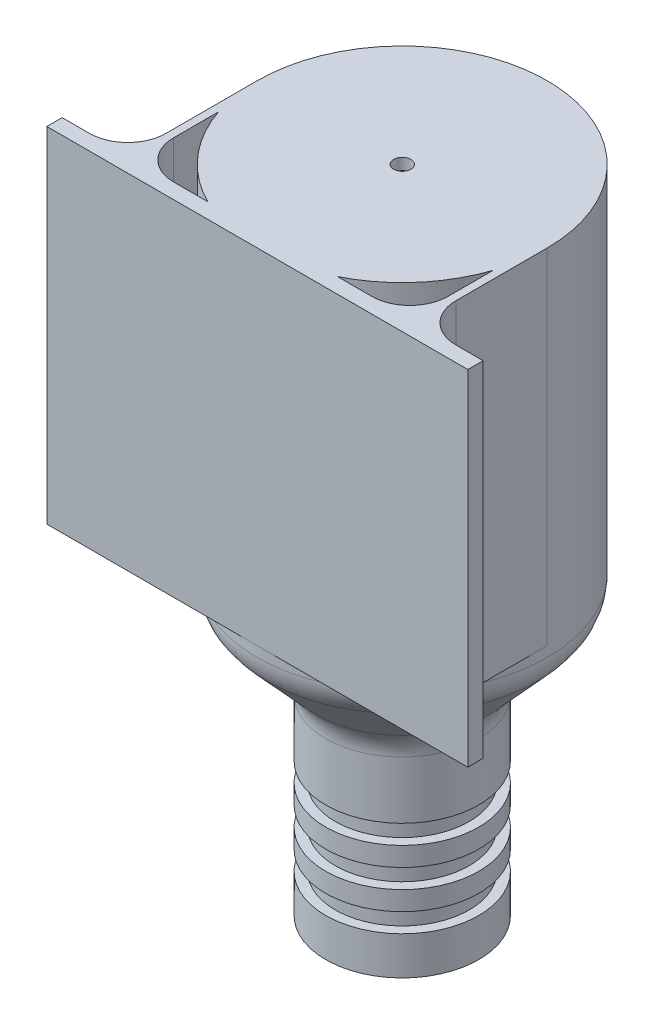
SolidWorks part; units mm, degrees
ref_plane "前视基准面" through (0, 0, 0) normal (0, 0, 1) x (1, 0, 0)
ref_plane "上视基准面" through (0, 0, 0) normal (0, 1, 0) x (1, 0, 0)
ref_plane "右视基准面" through (0, 0, 0) normal (1, 0, 0) x (0, 0, -1)
other "Configuration Table"
sketch "草图2" plane through (0, 0, 0) normal (0, 0, 1) x (1, 0, 0)
  line L0 (0, -59.8968) -> (0, -239.7168) construction
  line L1 (20, -224.4112) -> (20, -214.4112)
  line L2 (20, -214.4112) -> (17.5, -214.4112)
  line L3 (17.5, -214.4112) -> (17.5, -209.4112)
  line L4 (17.5, -209.4112) -> (20, -209.4112)
  line L5 (20, -209.4112) -> (20, -204.4112)
  line L6 (20, -204.4112) -> (17.5, -204.4112)
  line L7 (17.5, -204.4112) -> (17.5, -199.4112)
  line L8 (17.5, -199.4112) -> (20, -199.4112)
  line L9 (20, -199.4112) -> (20, -194.4112)
  line L10 (20, -194.4112) -> (17.5, -194.4112)
  line L11 (17.5, -194.4112) -> (17.5, -189.4112)
  line L12 (17.5, -189.4112) -> (20, -189.4112)
  line L13 (15.5, -224.4112) -> (15.5, -174.7923)
  line L16 (15.5, -224.4112) -> (20, -224.4112)
  line L17 (20, -189.4112) -> (20, -174.4112)
  line L18 (18.5713, -167.5817) -> (20.5164, -165.7126)
  line L19 (35.8731, -129.6594) -> (35.8731, -54.4112)
  line L20 (22.615, -167.6687) -> (35.2581, -153.8207)
  line L21 (37.8731, -147.0782) -> (37.8731, -54.4112)
  line L22 (37.8731, -54.4112) -> (35.8731, -54.4112)
  arc A0 (20.5164, -165.7126) -> (35.8731, -129.6594) centre (-14.1269, -129.6594) ccw
  arc A1 (35.2581, -153.8207) -> (37.8731, -147.0782) centre (27.8731, -147.0782) ccw
  arc A2 (15.5, -174.7923) -> (18.5713, -167.5817) centre (25.5, -174.7923) cw
  arc A3 (20, -174.4112) -> (22.615, -167.6687) centre (30, -174.4112) cw
  point P2 (0, 0)
  point P24 (0, 0)
  point P25 (0, 0)
  point P26 (15.8596, -172.1504)
  point P27 (18.2503, -189.4112)
  point P28 (35.8731, -152.574)
  point P31 (35.8731, -150.9565)
  point P34 (37.8731, -150.9565)
  point P37 (15.5, -170.5329)
  point P40 (20, -170.5329)
  point P41 (0, 0)
  point P42 (0, 0)
  point P43 (19.88, -226.0579)
  dimension "D13" = 50
  dimension "D14" = 10
  dimension "D15" = 10
  dimension "D2" = 2.5
  dimension "D3" = 5
  dimension "D4" = 2.5
  dimension "D5" = 5
  dimension "D6" = 2.5
  dimension "D7" = 5
  dimension "D8" = 5
  dimension "D9" = 10
  dimension "D10" = 5
  dimension "D11" = 2
  dimension "D12" = 2.5
  dimension "D16" = 120
  dimension "D17" = 50
  dimension "D18" = 40
  dimension "D19" = 2
revolve "旋转1" add sketch "草图2" angle 360 about L0
sketch "草图3" plane through (0, -54.4112, 0) normal (0, 1, 0) x (1, 0, 0)
  line L0 (0, 51.2049) -> (0, -52.2438) construction
  circle A1 centre (0, 0) radius 2.25
  circle A2 centre (0, 0) radius 37.8731 construction
  circle A4 centre (0, 0) radius 37.8731
  circle M1 centre (0, 0) radius 35.8731
  circle M2 centre (0, 0) radius 37.8731
  dimension "D1" = 4.5
sketch "草图4" plane through (0, -54.4112, 0) normal (0, 1, 0) x (1, 0, 0)
  line L0 (-37.8731, 0) -> (-37.8731, -23.8731)
  line L1 (-47.8731, -33.8731) -> (-55, -33.8731)
  line L2 (-55, -33.8731) -> (-55, -37.8731)
  line L3 (-55, -37.8731) -> (55, -37.8731)
  line L4 (0, 51.2049) -> (0, -52.2438) construction
  line L5 (0, -37.8731) -> (0, -33.8731) construction
  line L6 (25.8731, -33.8731) -> (-25.8731, -33.8731)
  line L7 (-35.8731, -23.8731) -> (-35.8731, 0)
  line L8 (-35.8731, 0) -> (-37.8731, 0)
  line L9 (35.8731, 0) -> (37.8731, 0)
  line L10 (35.8731, -23.8731) -> (35.8731, 0)
  line L11 (55, -33.8731) -> (55, -37.8731)
  line L12 (47.8731, -33.8731) -> (55, -33.8731)
  line L13 (37.8731, 0) -> (37.8731, -23.8731)
  circle A0 centre (0, 0) radius 37.8731 construction
  circle A1 centre (0, 0) radius 35.8731 construction
  circle A2 centre (0, 0) radius 35.8731 construction
  arc A3 (-37.8731, -23.8731) -> (-47.8731, -33.8731) centre (-47.8731, -23.8731) cw
  arc A4 (-25.8731, -33.8731) -> (-35.8731, -23.8731) centre (-25.8731, -23.8731) cw
  arc A5 (25.8731, -33.8731) -> (35.8731, -23.8731) centre (25.8731, -23.8731) ccw
  arc A6 (37.8731, -23.8731) -> (47.8731, -33.8731) centre (47.8731, -23.8731) ccw
  circle M8 centre (0, 0) radius 35.8731
  circle M9 centre (0, 0) radius 37.8731
  dimension "D3" = 10
  dimension "D1" = 2
  dimension "D2" = 4
  dimension "D4" = 55
extrude "凸台-拉伸1" add sketch "草图4" against normal blind 90 contours L6 A4 L7 L0 A3 L1 L2 L3 M9 | A6 L13 L10 A5 L6 L3 L11 L12 M9 | L5 L6 M9 M8 | L5 L6 M9 M8
extrude "凸台-拉伸2" add sketch "草图3" against normal blind 3 contours L0 A1 M1 | L0 A1 M1 | L0 A4 M1 | L0 M2 M1
